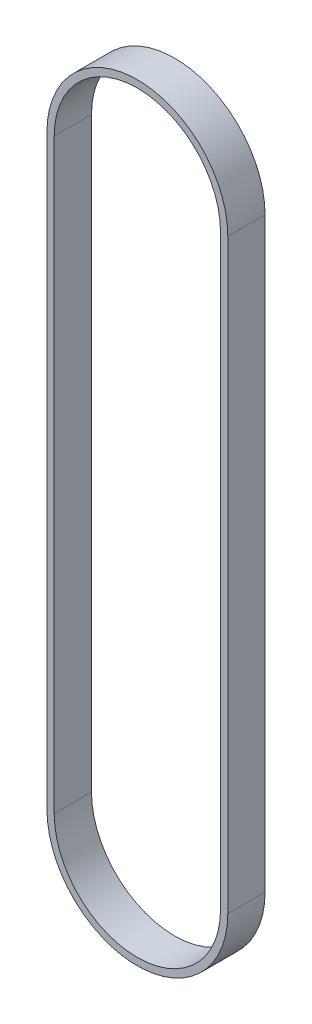
SolidWorks part; units mm, degrees
ref_plane "前视基准面" through (0, 0, 0) normal (0, 0, 1) x (1, 0, 0)
ref_plane "上视基准面" through (0, 0, 0) normal (0, 1, 0) x (1, 0, 0)
ref_plane "右视基准面" through (0, 0, 0) normal (1, 0, 0) x (0, 0, -1)
sketch "草图1" plane through (0, 0, 0) normal (0, 0, 1) x (1, 0, 0)
  line L0 (-23.12, 0) -> (-23.12, -150)
  line L2 (0, -21.265) -> (0, -128.8161) construction
  line L3 (0, -171.1839) -> (0, -207.4638) construction
  line L4 (23.12, 0) -> (23.12, -150)
  line L5 (-21.265, 0) -> (-21.265, -150)
  line L6 (21.265, 0) -> (21.265, -150)
  arc A0 (21.265, 0) -> (-21.265, 0) centre (0, 0) ccw
  arc A1 (23.12, 0) -> (-23.12, 0) centre (0, 0) ccw
  arc A4 (-23.12, -150) -> (23.12, -150) centre (0, -150) ccw
  arc A5 (-21.265, -150) -> (21.265, -150) centre (0, -150) ccw
  dimension "D1" = 150
  dimension "D2" = 42.53
  dimension "D3" = 46.24
extrude "凸台-拉伸5" add sketch "草图1" along normal blind 9.529
